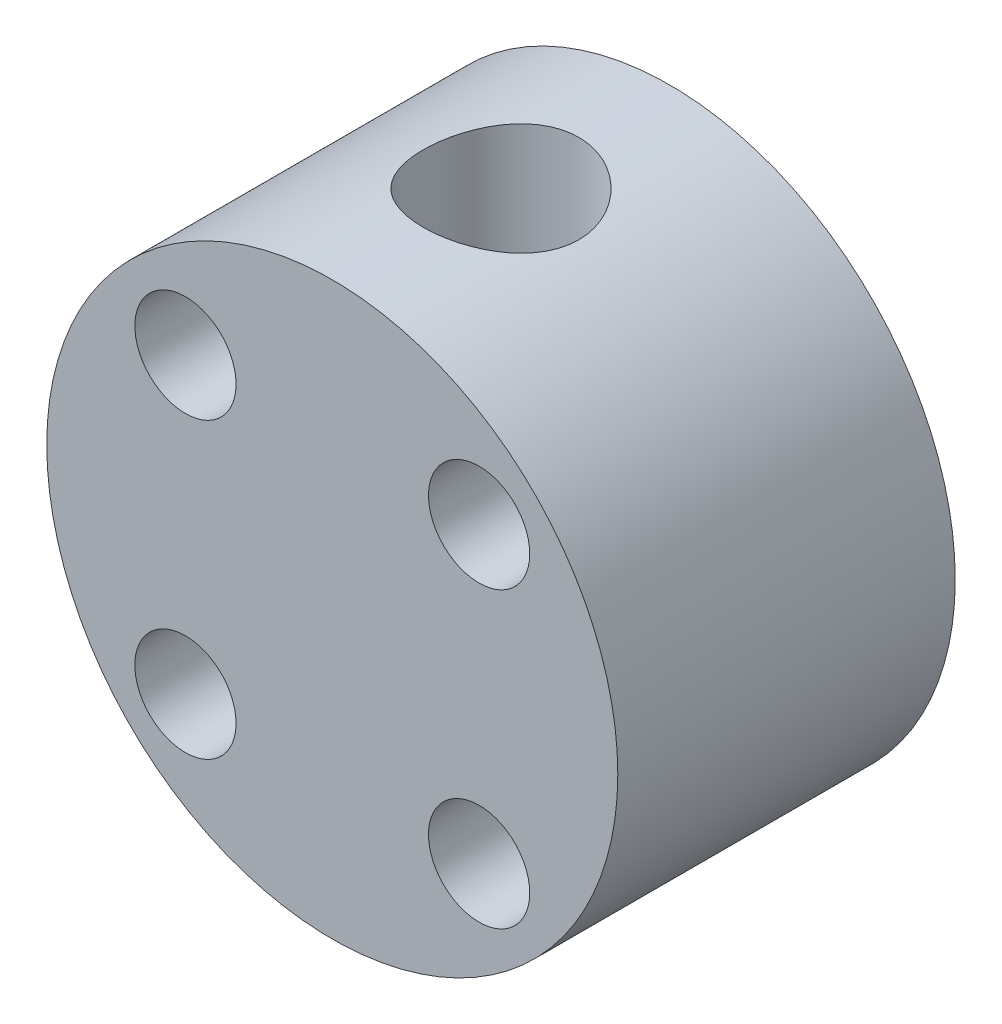
SolidWorks part; units mm, degrees
material "ABS"
ref_plane "Front Plane" through (0, 0, 0) normal (0, 0, 1) x (1, 0, 0)
ref_plane "Top Plane" through (0, 0, 0) normal (0, 1, 0) x (1, 0, 0)
ref_plane "Right Plane" through (0, 0, 0) normal (1, 0, 0) x (0, 0, -1)
sketch "Sketch1" plane through (0, 0, 0) normal (0, 0, 1) x (1, 0, 0)
  circle A0 centre (0, 0) radius 11
  dimension "D1" = 22
extrude "Boss-Extrude1" add sketch "Sketch1" along normal mid plane 13
sketch "Sketch2" plane through (0, 0, 0) normal (0, 1, 0) x (1, 0, 0)
  circle A0 centre (0, 0) radius 3
  dimension "D1" = 6
extrude "Cut-Extrude1" cut sketch "Sketch2" against normal through all both and the other way through all
hole_wizard "M3 Clearance Hole1" positions "Sketch3" profile "Sketch4" hole size "M3" standard "ANSI Metric" end condition up to next
sketch "Sketch3" plane through (0, 0, 6.5) normal (0, 0, 1) x (1, 0, 0)
  line L1 (-5.6569, -5.6569) -> (5.6569, -5.6569) construction
  line L2 (-5.6569, -5.6569) -> (-5.6569, 5.6569) construction
  line L3 (-5.6569, 5.6569) -> (5.6569, 5.6569) construction
  line L4 (5.6569, -5.6569) -> (5.6569, 5.6569) construction
  line L5 (-5.6569, -5.6569) -> (5.6569, 5.6569) construction
  line L6 (-5.6569, 5.6569) -> (5.6569, -5.6569) construction
  point P2 (5.6569, 5.6569)
  point P37 (-5.6569, -5.6569)
  point P38 (-5.6569, 5.6569)
  point P39 (5.6569, -5.6569)
  dimension "D1" = 16
sketch "Sketch4" plane through (5.6569, 5.6569, 6.5) normal (1, 0, 0) x (0, -1, 0)
  line L0 (0, 0) -> (0, 13)
  line L1 (0, 13) -> (1.95, 13)
  line L2 (1.95, 13) -> (1.95, 0)
  line L5 (1.95, 0) -> (0, 0)
  line L11 (0, -6.35) -> (0, 107.95) construction
  dimension "Thru Hole Dia." = 3.9
  dimension "Thru Hole Depth" = 13
